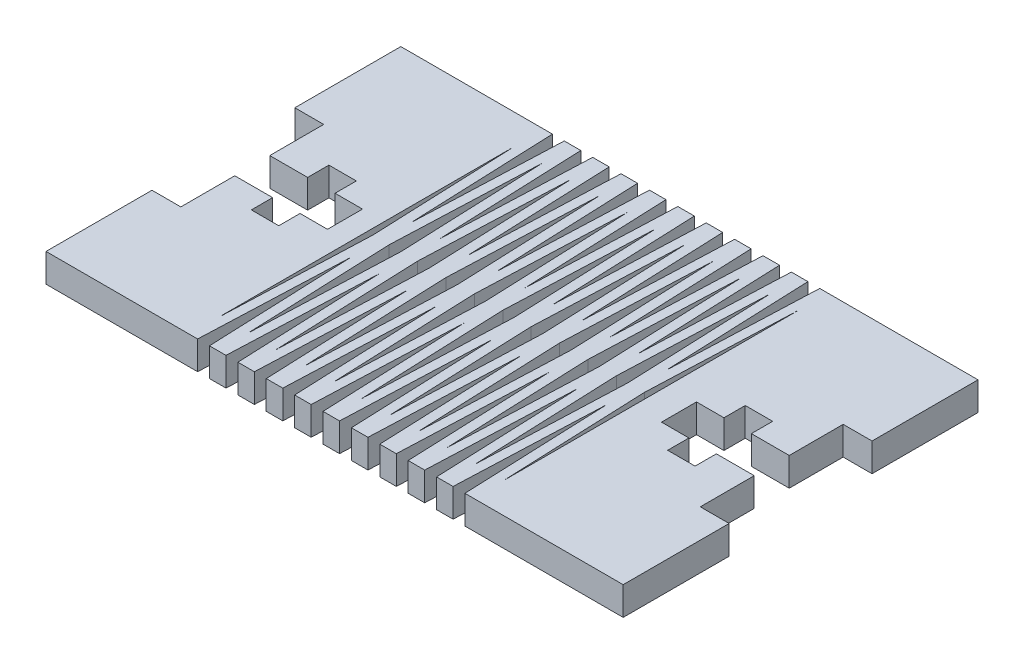
SolidWorks part; units mm, degrees
ref_plane "Front" through (0, 0, 0) normal (0, 0, 1) x (1, 0, 0)
ref_plane "Top" through (0, 0, 0) normal (0, 1, 0) x (1, 0, 0)
ref_plane "Right" through (0, 0, 0) normal (1, 0, 0) x (0, 0, -1)
sketch "Sketch1" plane through (0, 0, 0) normal (0, 1, 0) x (1, 0, 0)
  line L1 (-30.5, 18.75) -> (30.5, 18.75)
  line L2 (-30.5, 18.75) -> (-30.5, -18.75)
  line L3 (-30.5, -18.75) -> (30.5, -18.75)
  line L4 (30.5, 18.75) -> (30.5, -18.75)
  line L5 (-30.5, 18.75) -> (30.5, -18.75) construction
  line L6 (-30.5, -18.75) -> (30.5, 18.75) construction
  point P0 (0, 0)
  dimension "D1" = 37.5
  dimension "D2" = 61
extrude "Boss-Extrude1" add sketch "Sketch1" along normal blind 3
sketch "Sketch3" plane through (0, 3, 0) normal (0, 1, 0) x (1, 0, 0)
  line L0 (30.5, 7.55) -> (27.45, 7.55)
  line L1 (30.5, -18.75) -> (30.5, 18.75) construction
  line L2 (27.45, 7.55) -> (27.45, 1.85)
  line L3 (27.45, 1.85) -> (23.45, 1.85)
  line L4 (23.45, 1.85) -> (23.45, 4.1)
  line L5 (23.45, 4.1) -> (20.55, 4.1)
  line L6 (20.55, 4.1) -> (20.55, 1.85)
  line L7 (20.55, 1.85) -> (17.65, 1.85)
  line L8 (17.65, 1.85) -> (17.65, 0)
  line L9 (17.65, 0) -> (30.5, 0)
  line L10 (30.5, 0) -> (30.5, 7.55)
  dimension "D1" = 3.05
  dimension "D2" = 7.55
  dimension "D3" = 4.1
  dimension "D4" = 2.9
  dimension "D5" = 4
  dimension "D6" = 9.8
  dimension "D7" = 1.85
extrude "Cut-Extrude2" cut sketch "Sketch3" against normal through all
mirror "Mirror1" about plane through (0, 0, 0) normal (0, 0, 1) of "Cut-Extrude2"
mirror "Mirror2" about plane through (0, 0, 0) normal (1, 0, 0) of "Mirror1", "Cut-Extrude2"
sketch "Sketch4" plane through (0, 3, 0) normal (0, 1, 0) x (1, 0, 0)
  line L0 (14.65, 15.575) -> (14.65, -15.575)
  line L1 (14.65, -15.575) -> (14.023, 0)
  line L2 (14.023, 0) -> (14.65, 15.575)
  line L3 (13.777, 18.75) -> (13.15, 3.175)
  line L4 (13.15, 3.175) -> (12.523, 18.75)
  line L5 (12.523, 18.75) -> (13.777, 18.75)
  line L6 (13.15, -3.175) -> (12.523, -18.75)
  line L7 (12.523, -18.75) -> (13.777, -18.75)
  line L8 (13.777, -18.75) -> (13.15, -3.175)
  line L9 (14.023, 0) -> (0, 0) construction
  line L10 (17.65, 1.85) -> (17.65, -1.85) construction
  line L11 (13.15, -3.175) -> (13.15, -18.75) construction
  line L12 (13.15, -3.175) -> (13.15, 3.175) construction
  line L13 (11.65, 15.575) -> (11.65, -15.575)
  line L14 (11.65, -15.575) -> (12.277, 0)
  line L15 (12.277, 0) -> (11.65, 15.575)
  line L16 (11.65, -15.575) -> (12.523, -18.75) construction
  line L17 (13.777, -18.75) -> (14.65, -15.575) construction
  line L18 (-30.5, -18.75) -> (30.5, -18.75) construction
  line L19 (30.5, 18.75) -> (-30.5, 18.75) construction
  dimension "D1" = 1
  dimension "D2" = 3.175
  dimension "D3" = 6.35
  dimension "D4" = 1.5
  dimension "D5" = 3
extrude "Cut-Extrude3" cut sketch "Sketch4" against normal through all
pattern_linear "LPattern1" count 10 spacing 3 along (-1, 0, 0) of "Cut-Extrude3"
